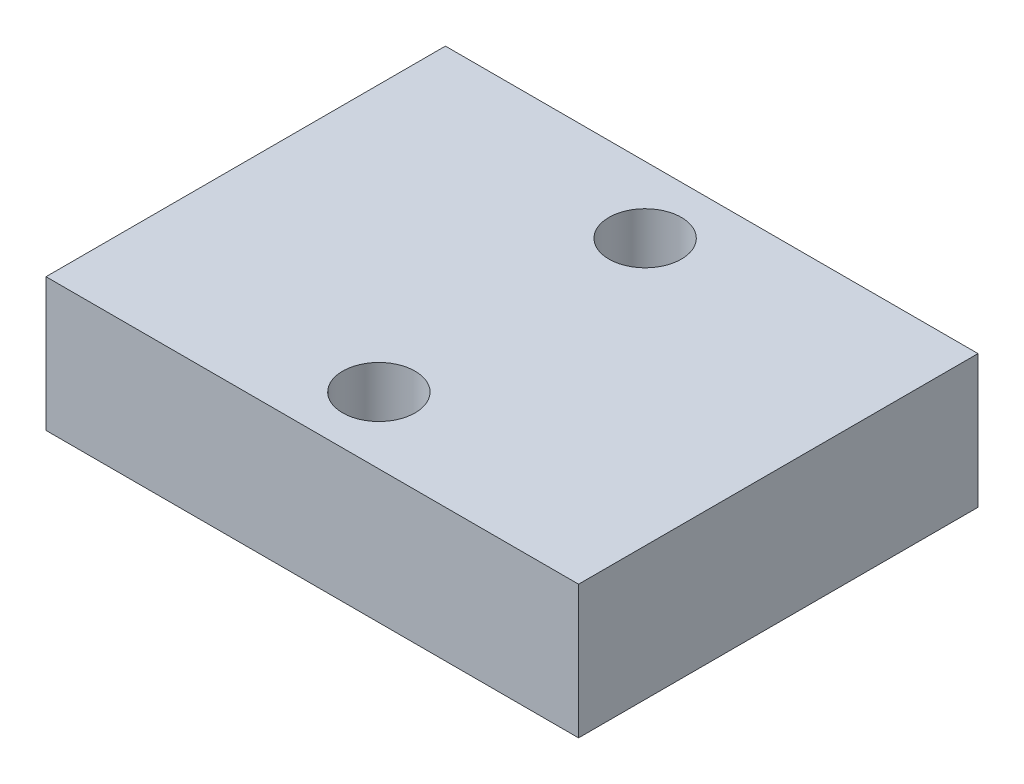
SolidWorks part; units mm, degrees
ref_plane "Front Plane" through (0, 0, 0) normal (0, 0, 1) x (1, 0, 0)
ref_plane "Top Plane" through (0, 0, 0) normal (0, 1, 0) x (1, 0, 0)
ref_plane "Right Plane" through (0, 0, 0) normal (1, 0, 0) x (0, 0, -1)
sketch "Sketch1" plane through (0, 0, 0) normal (0, 1, 0) x (1, 0, 0)
  line L1 (-12.7, 9.525) -> (12.7, 9.525)
  line L2 (-12.7, 9.525) -> (-12.7, -9.525)
  line L3 (-12.7, -9.525) -> (12.7, -9.525)
  line L4 (12.7, 9.525) -> (12.7, -9.525)
  line L5 (-12.7, 9.525) -> (12.7, -9.525) construction
  line L6 (-12.7, -9.525) -> (12.7, 9.525) construction
  point P0 (0, 0)
  dimension "D1" = 25.4
  dimension "D2" = 19.05
extrude "Boss-Extrude1" add sketch "Sketch1" along normal mid plane 6.35
hole_wizard "#8-32 Tapped Hole1" positions "Sketch3" profile "Sketch2" tap size "#8-32" standard "ANSI Inch" end condition up to next
sketch "Sketch3" plane through (0, 3.175, 0) normal (0, 1, 0) x (1, 0, 0)
  point P0 (0, 6.35)
  point P2 (0, -6.35)
  dimension "D1" = 6.35
  dimension "D2" = 6.35
sketch "Sketch2" plane through (0, 3.175, -6.35) normal (1, 0, 0) x (0, 0, 1)
  line L0 (0, 0) -> (0, 6.35)
  line L1 (0, 6.35) -> (1.7272, 6.35)
  line L2 (1.7272, 6.35) -> (1.7272, 0)
  line L5 (1.7272, 0) -> (0, 0)
  line L11 (0, -6.35) -> (0, 107.95) construction
  dimension "Thru Tap Drill Dia." = 3.4544
  dimension "Thru Tap Drill Depth" = 6.35
cosmetic thread "Hole Thread1" parameters "D2"=4.1656
cosmetic thread "Hole Thread2" parameters "D2"=4.1656
